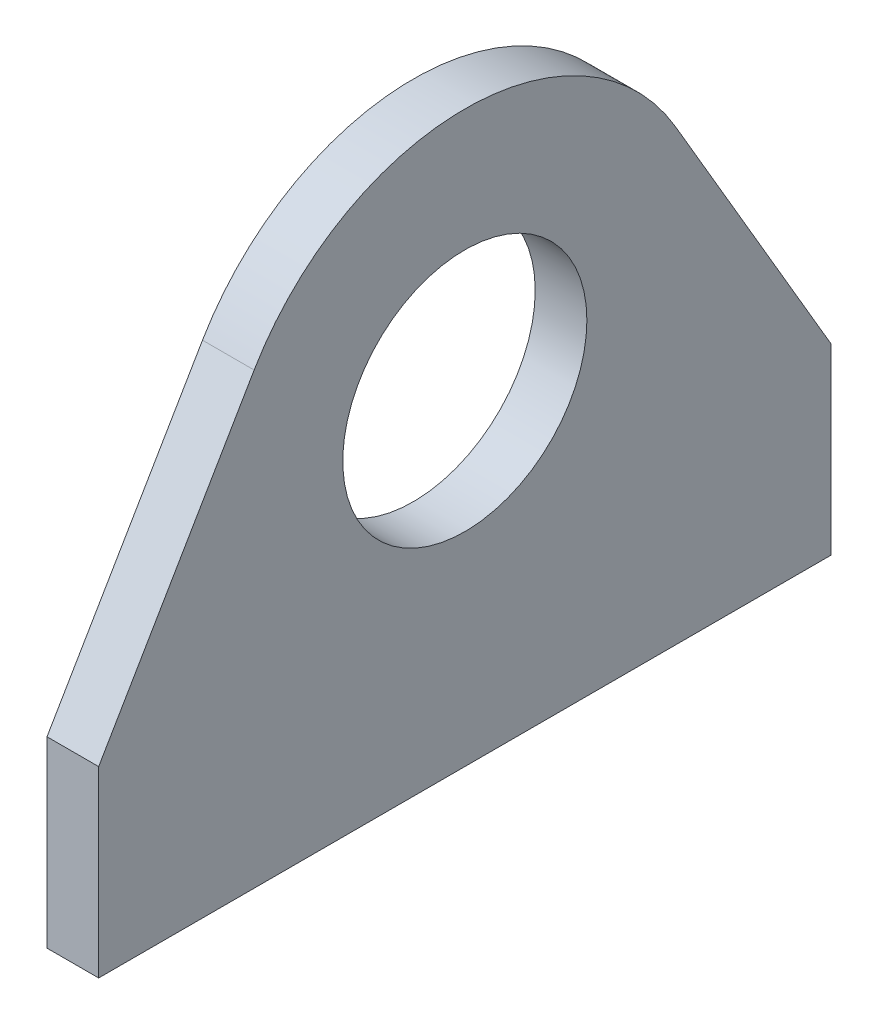
SolidWorks part; units mm, degrees
ref_plane "Front Plane" through (0, 0, 0) normal (0, 0, 1) x (1, 0, 0)
ref_plane "Top Plane" through (0, 0, 0) normal (0, 1, 0) x (1, 0, 0)
ref_plane "Right Plane" through (0, 0, 0) normal (1, 0, 0) x (0, 0, -1)
sketch "Sketch1" plane through (0, 0, 0) normal (1, 0, 0) x (0, 0, -1)
  line L0 (-35.4235, 0) -> (41.5461, 0) construction
  line L1 (0, 153.9113) -> (0, -38.9221) construction
  line L3 (90, 0) -> (90, 45)
  line L4 (90, 45) -> (51.7849, 110.3039)
  line L5 (35.4235, 0) -> (-41.5461, 0) construction
  line L6 (-90, 45) -> (-51.7849, 110.3039)
  line L7 (-90, 0) -> (-90, 45)
  line L8 (-90, 0) -> (90, 0)
  arc A0 (51.7849, 110.3039) -> (-51.7849, 110.3039) centre (0, 80) ccw
  circle A1 centre (0, 80) radius 30
  point P22 (0, 0)
  dimension "D3" = 60
  dimension "D4" = 180
  dimension "D5" = 140
  dimension "D6" = 60
  dimension "D1" = 90
  dimension "D2" = 45
extrude "Boss-Extrude1" add sketch "Sketch1" along normal mid plane 12.7
